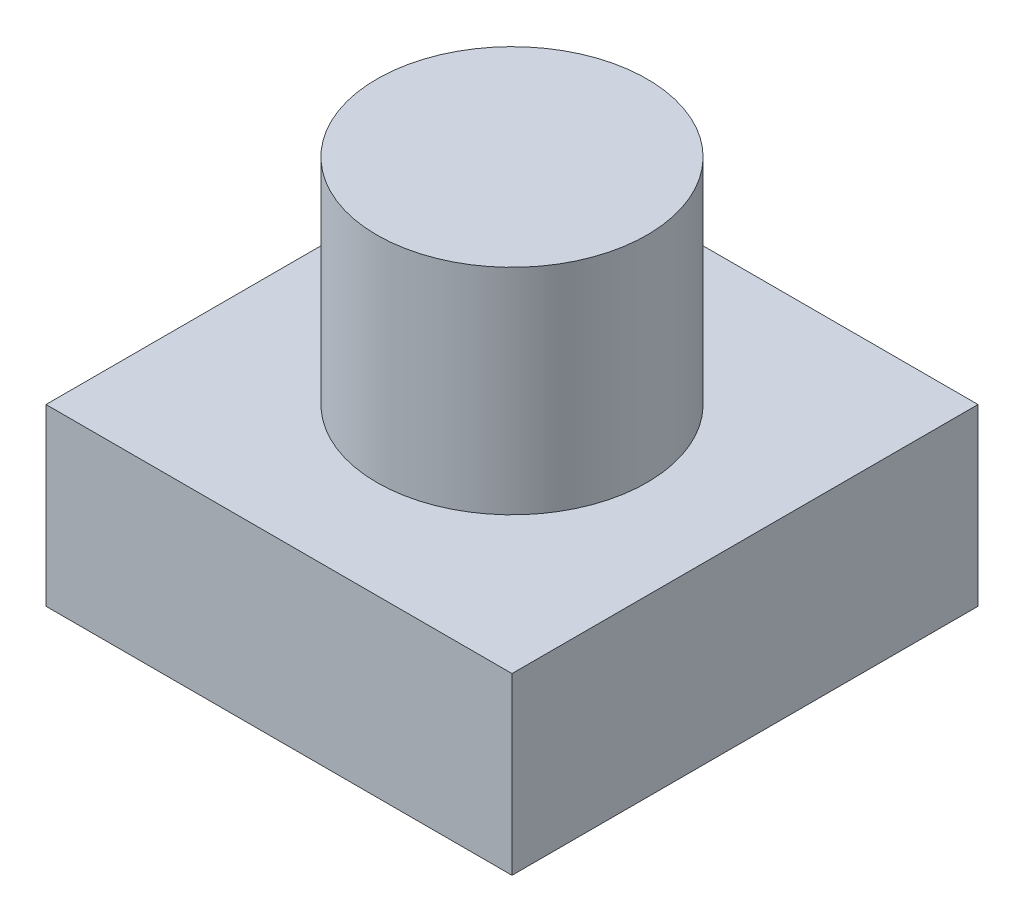
SolidWorks part; units mm, degrees
ref_plane "Front Plane" through (0, 0, 0) normal (0, 0, 1) x (1, 0, 0)
ref_plane "Top Plane" through (0, 0, 0) normal (0, 1, 0) x (1, 0, 0)
ref_plane "Right Plane" through (0, 0, 0) normal (1, 0, 0) x (0, 0, -1)
sketch "Sketch1" plane through (0, 0, 0) normal (0, 1, 0) x (1, 0, 0)
  circle A0 centre (0, 0) radius 3.683
  dimension "D1" = 7.366
extrude "Boss-Extrude1" add sketch "Sketch1" along normal blind 5.842
sketch "Sketch2" plane through (0, 0, 0) normal (0, -1, 0) x (1, 0, 0)
  line L1 (6.35, 6.35) -> (-6.35, 6.35)
  line L2 (6.35, 6.35) -> (6.35, -6.35)
  line L3 (6.35, -6.35) -> (-6.35, -6.35)
  line L4 (-6.35, 6.35) -> (-6.35, -6.35)
  line L5 (6.35, 6.35) -> (-6.35, -6.35) construction
  line L6 (6.35, -6.35) -> (-6.35, 6.35) construction
  point P0 (0, 0)
  dimension "D1" = 12.7
extrude "Boss-Extrude2" add sketch "Sketch2" along normal blind 4.7625
